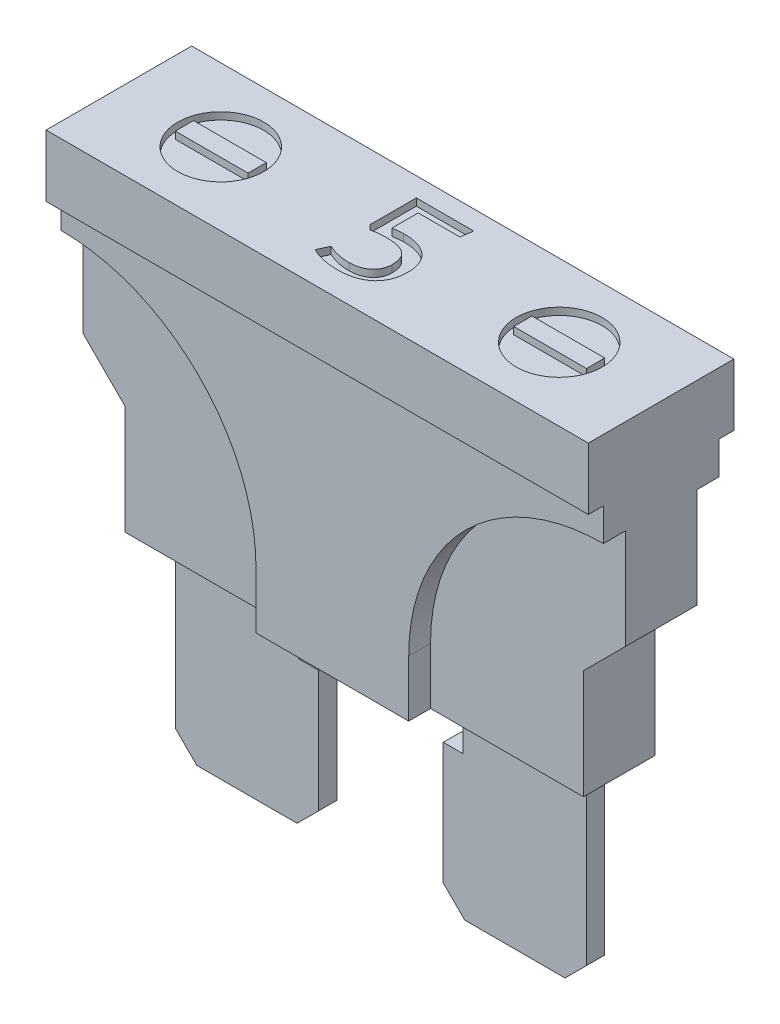
SolidWorks part; units mm, degrees
ref_plane "Front Plane" through (0, 0, 0) normal (0, 0, 1) x (1, 0, 0)
ref_plane "Top Plane" through (0, 0, 0) normal (0, 1, 0) x (1, 0, 0)
ref_plane "Right Plane" through (0, 0, 0) normal (1, 0, 0) x (0, 0, -1)
sketch "Sketch3" plane through (0, 0, 0) normal (0, 0, 1) x (1, 0, 0)
  line L10 (-7.1755, 5.2705) -> (-7.1755, -12.7755)
  line L11 (-7.1755, -12.7755) -> (-6.4255, -13.5255)
  line L12 (-6.4255, -13.5255) -> (-2.9255, -13.5255)
  line L13 (-2.9255, -13.5255) -> (-2.1755, -12.7755)
  line L14 (-2.1755, -12.7755) -> (-2.1755, -8.5255)
  line L15 (-2.1755, -8.5255) -> (-2.8575, -8.5255)
  line L16 (-2.8575, -8.5255) -> (-2.8575, -4.6355)
  line L17 (-2.8575, -4.6355) -> (-2.2145, -4.6355)
  line L18 (2.8575, -4.6355) -> (2.8575, -8.5255)
  line L19 (2.8575, -8.5255) -> (2.1755, -8.5255)
  line L20 (2.1755, -8.5255) -> (2.1755, -12.7755)
  line L21 (2.1755, -12.7755) -> (2.9255, -13.5255)
  line L22 (2.9255, -13.5255) -> (6.4255, -13.5255)
  line L23 (6.4255, -13.5255) -> (7.1755, -12.7755)
  line L24 (7.1755, -12.7755) -> (7.1755, 5.2705)
  line L27 (7.1755, 5.2705) -> (4.6355, 5.2705)
  line L28 (4.6355, 5.2705) -> (4.6355, 1.7145)
  line L29 (4.6355, 1.7145) -> (2.8575, 1.7145)
  line L30 (2.8575, 1.7145) -> (2.8575, -4.1355)
  line L31 (2.8575, -4.1355) -> (2.2145, -4.1355)
  line L32 (-2.8575, -4.1355) -> (-2.8575, 1.7145)
  line L33 (-2.8575, 1.7145) -> (-4.6355, 1.7145)
  line L34 (-4.6355, 1.7145) -> (-4.6355, 5.2705)
  line L35 (-4.6355, 5.2705) -> (-7.1755, 5.2705)
  line L36 (2.2145, -4.6355) -> (2.8575, -4.6355)
  line L37 (-1.7145, -3.6355) -> (-1.7145, 0)
  line L38 (1.7145, -3.6355) -> (1.7145, 0)
  line L40 (-1.2145, -3.6355) -> (-1.2145, 0)
  line L41 (1.2145, -3.6355) -> (1.2145, 0)
  line L43 (-2.2145, -4.1355) -> (-2.8575, -4.1355)
  line L44 (-2.1755, -10.6505) -> (-7.1755, -10.6505) construction
  line L45 (2.536, -4.1355) -> (2.536, -4.6355) construction
  line L46 (-1.7145, -4.1355) -> (-1.2145, -4.1355) construction
  line L47 (1.7145, -4.1355) -> (1.2145, -4.1355) construction
  line L48 (2.1755, -10.6505) -> (7.1755, -10.6505) construction
  line L49 (-4.6755, -13.5255) -> (-4.6755, -10.6505) construction
  line L50 (4.6755, -13.5255) -> (4.6755, -10.6505) construction
  line L51 (5.0165, -4.1355) -> (5.0165, -10.6505) construction
  line L52 (-5.6515, -2.1035) -> (-4.3815, -2.1035)
  line L53 (-5.6515, -2.1035) -> (-5.6515, -4.1355)
  line L54 (-5.6515, -4.1355) -> (-4.3815, -4.1355)
  line L55 (-4.3815, -2.1035) -> (-4.3815, -4.1355)
  line L56 (4.3815, -2.1035) -> (5.6515, -2.1035)
  line L57 (4.3815, -2.1035) -> (4.3815, -4.1355)
  line L58 (4.3815, -4.1355) -> (5.6515, -4.1355)
  line L59 (5.6515, -2.1035) -> (5.6515, -4.1355)
  line L60 (-5.0165, -4.1355) -> (-5.0165, -10.6505) construction
  line L61 (-1.8609, -3.9891) -> (-1.5074, -4.3426) construction
  arc A1 (1.7145, 0) -> (-1.7145, 0) centre (0, 0) ccw
  arc A3 (1.2145, 0) -> (-1.2145, 0) centre (0, 0) ccw
  arc A4 (2.2145, -4.6355) -> (1.2145, -3.6355) centre (2.2145, -3.6355) cw
  arc A5 (-2.2145, -4.6355) -> (-1.2145, -3.6355) centre (-2.2145, -3.6355) ccw
  arc A6 (1.7145, -3.6355) -> (2.2145, -4.1355) centre (2.2145, -3.6355) ccw
  arc A7 (-1.7145, -3.6355) -> (-2.2145, -4.1355) centre (-2.2145, -3.6355) cw
  point P62 (-1.8609, -3.9891)
  point P69 (1.8609, -3.9891)
  dimension "D14" = 1
  dimension "D1" = 2.54
  dimension "D2" = 3.556
  dimension "D3" = 4.318
  dimension "D4" = 14.351
  dimension "D5" = 18.796
  dimension "D6" = 8.89
  dimension "D7" = 3.429
  dimension "D8" = 0.5
  dimension "D9" = 5
  dimension "D10" = 3.5
  dimension "D11" = 5
  dimension "D12" = 2.032
  dimension "D13" = 1.27
extrude "Boss-Extrude2" add sketch "Sketch3" along normal mid plane 0.635
ref_plane "Plane1" through (0, -6.7945, 0) normal (0, -1, 0) x (-1, 0, 0)
sketch "Sketch4" plane through (0, -6.7945, 0) normal (0, -1, 0) x (-1, 0, 0)
  line L0 (5.0165, 1.25) -> (5.0165, -1.25) construction
  line L1 (8.001, -1.25) -> (2.032, -1.25)
  line L2 (8.001, -1.25) -> (8.001, 1.25)
  line L3 (8.001, 1.25) -> (2.032, 1.25)
  line L4 (2.032, -1.25) -> (2.032, 1.25)
  line L5 (-2.032, -1.25) -> (-8.001, -1.25)
  line L6 (-2.032, -1.25) -> (-2.032, 1.25)
  line L7 (-2.032, 1.25) -> (-8.001, 1.25)
  line L8 (-8.001, -1.25) -> (-8.001, 1.25)
  line L9 (-5.0165, 1.25) -> (-5.0165, -1.25) construction
  line L10 (7.1755, 0) -> (2.8575, 0) construction
  line L11 (7.1755, -0.3175) -> (7.1755, 0.3175) construction
  line L13 (-2.8575, 0) -> (-7.1755, 0) construction
  line L15 (-7.1755, -0.3175) -> (-7.1755, 0.3175) construction
  line L16 (-2.8575, -0.3175) -> (-2.8575, 0.3175) construction
  line L17 (2.8575, -0.3175) -> (2.8575, 0.3175) construction
  dimension "D1" = 16.002
  dimension "D2" = 2.5
extrude "Boss-Extrude3" add sketch "Sketch4" against normal blind 10.16 separate body
sketch "Sketch6" plane through (0, 0, 1.25) normal (0, 0, 1) x (1, 0, 0)
  line L0 (-2.665, -6.7945) -> (2.665, -6.7945)
  line L3 (-9.4615, 1.9685) -> (9.4615, 1.9685) construction
  line L4 (0, 0) -> (0, -6.7945) construction
  line L5 (-9.4615, 1.9685) -> (-9.4615, 5.2705)
  line L6 (-9.4615, 5.2705) -> (9.4615, 5.2705)
  line L7 (9.4615, 5.2705) -> (9.4615, 1.9685)
  line L8 (7.1755, 5.2705) -> (4.6355, 5.2705) construction
  line L9 (-2.665, -4.828) -> (-2.665, -6.7945)
  line L10 (2.665, -4.828) -> (2.665, -6.7945)
  line L11 (8.001, -6.7945) -> (2.032, -6.7945) construction
  arc A0 (9.4615, 1.9685) -> (2.665, -4.828) centre (9.4615, -4.828) ccw
  arc A1 (-2.665, -4.828) -> (-9.4615, 1.9685) centre (-9.4615, -4.828) ccw
  dimension "D1" = 5.33
  dimension "D2" = 18.923
  dimension "D3" = 3.302
extrude "Boss-Extrude4" add sketch "Sketch6" along normal blind 0.762
mirror "Mirror1" about plane through (0, 0, 0) normal (0, 0, 1) of "Boss-Extrude4"
sketch "Sketch7" plane through (0, 5.2705, 0) normal (0, 1, 0) x (1, 0, 0)
  line L1 (9.4615, -2.54) -> (-9.4615, -2.54)
  line L2 (9.4615, -2.54) -> (9.4615, 2.54)
  line L3 (9.4615, 2.54) -> (-9.4615, 2.54)
  line L4 (-9.4615, -2.54) -> (-9.4615, 2.54)
  line L5 (9.4615, -2.54) -> (-9.4615, 2.54) construction
  line L6 (9.4615, 2.54) -> (-9.4615, -2.54) construction
  point P0 (0, 0)
  dimension "D1" = 5.08
  dimension "D2" = 18.923
extrude "Boss-Extrude5" add sketch "Sketch7" against normal blind 2.159
sketch "Sketch9" plane through (0, 5.2705, 0) normal (0, 1, 0) x (1, 0, 0)
  line L0 (5.9055, -0.3175) -> (5.9055, 0.3175) construction
  line L1 (7.1755, -0.3175) -> (4.6355, -0.3175) construction
  line L2 (7.1755, 0.3175) -> (4.6355, 0.3175) construction
  line L3 (-5.9055, -0.3175) -> (-5.9055, 0.3175) construction
  line L4 (-4.6355, -0.3175) -> (-7.1755, -0.3175) construction
  line L5 (-4.6355, 0.3175) -> (-7.1755, 0.3175) construction
  line L6 (-2.665, -1.631) -> (2.665, -1.631) construction
  line L8 (2.665, -2.012) -> (2.665, -1.25) construction
  line L11 (-2.665, -2.012) -> (-2.665, -1.25) construction
  circle A0 centre (5.9055, 0) radius 1.5
  circle A1 centre (-5.9055, 0) radius 1.5
  text T0 "5" font "Dubai" height 3.5
  dimension "D1" = 3
extrude "Cut-Extrude1" cut sketch "Sketch9" against normal blind 0.25
sketch "Sketch10" plane through (0, 0, 0) normal (0, 0, 1) x (1, 0, 0)
  line L0 (-9.4615, 3.1115) -> (-9.4615, -1.524)
  line L1 (-9.4615, -1.524) -> (-8.001, -2.9845)
  line L2 (-8.001, 1.8097) -> (-8.001, -6.7945) construction
  line L3 (-8.001, -2.9845) -> (-8.001, 3.1115)
  line L4 (9.4615, 3.1115) -> (-9.4615, 3.1115) construction
  line L5 (-8.001, 3.1115) -> (-9.4615, 3.1115)
  line L6 (8.001, 3.1115) -> (8.001, -2.9845)
  line L7 (8.001, 1.8097) -> (8.001, -6.7945) construction
  line L8 (8.001, -2.9845) -> (9.4615, -1.524)
  line L9 (9.4615, -1.524) -> (9.4615, 3.1115)
  line L10 (9.4615, 3.1115) -> (8.001, 3.1115)
  line L11 (-2.665, -6.7945) -> (-8.001, -6.7945) construction
  dimension "D1" = 3.81
extrude "Boss-Extrude6" add sketch "Sketch10" along normal mid plane 2.5
sketch "Sketch11" plane through (0, -6.7945, 0) normal (0, -1, 0) x (1, 0, 0)
  line L0 (-4.6355, 0.3175) -> (-7.1755, 0.3175) construction
  line L1 (2.8575, -0.3175) -> (-2.8575, -0.3175)
  line L2 (2.8575, -0.3175) -> (2.8575, 0.3175)
  line L3 (2.8575, 0.3175) -> (-2.8575, 0.3175)
  line L4 (-2.8575, -0.3175) -> (-2.8575, 0.3175)
  line L5 (2.8575, 0.3175) -> (2.8575, -0.3175) construction
  line L6 (4.3815, -0.3175) -> (5.6515, -0.3175) construction
  line L7 (-2.8575, 0.3175) -> (-2.8575, -0.3175) construction
extrude "Cut-Extrude2" cut sketch "Sketch11" against normal up to vertex (2.659 mm away) up to point (-2.8575, -4.1355, -0.3175)
